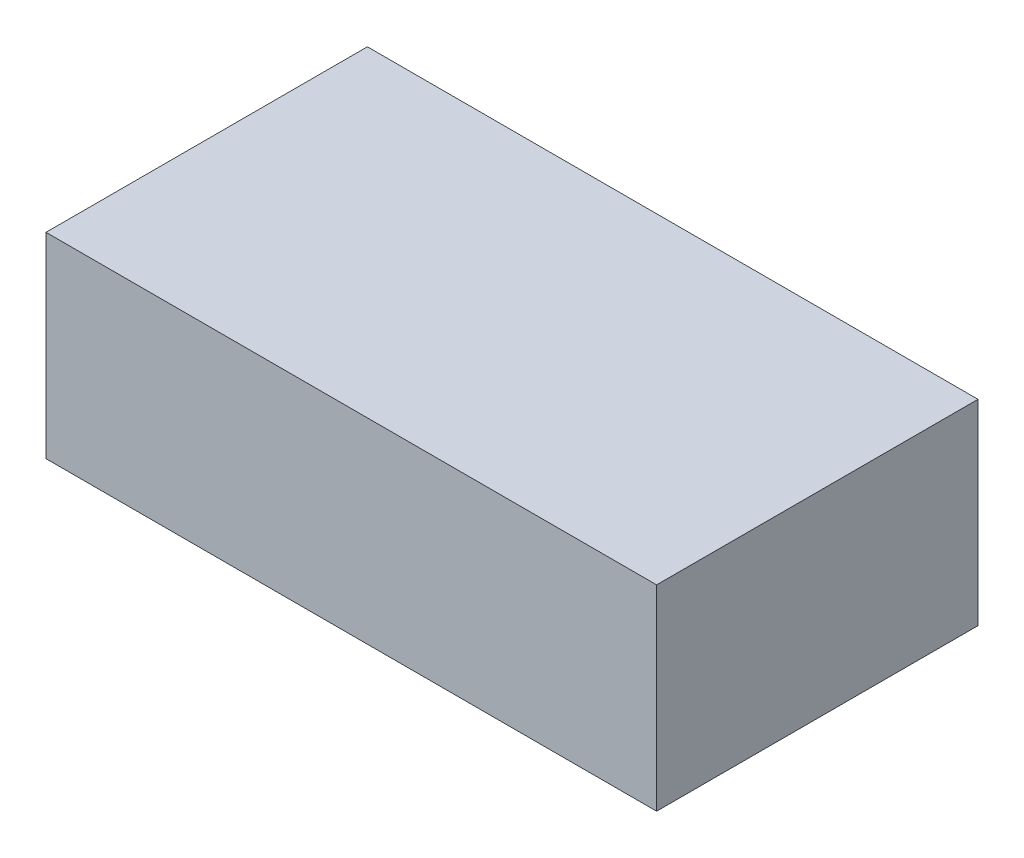
SolidWorks part; units mm, degrees
ref_plane "Front Plane" through (0, 0, 0) normal (0, 0, 1) x (1, 0, 0)
ref_plane "Top Plane" through (0, 0, 0) normal (0, 1, 0) x (1, 0, 0)
ref_plane "Right Plane" through (0, 0, 0) normal (1, 0, 0) x (0, 0, -1)
sketch "Sketch1" plane through (0, 0, 0) normal (0, 1, 0) x (1, 0, 0)
  line L1 (-48.26, 0) -> (0, 0)
  line L2 (-48.26, 0) -> (-48.26, -25.4)
  line L3 (-48.26, -25.4) -> (0, -25.4)
  line L4 (0, 0) -> (0, -25.4)
  dimension "D1" = 48.26
  dimension "D2" = 25.4
extrude "Boss-Extrude1" add sketch "Sketch1" along normal blind 15.494
